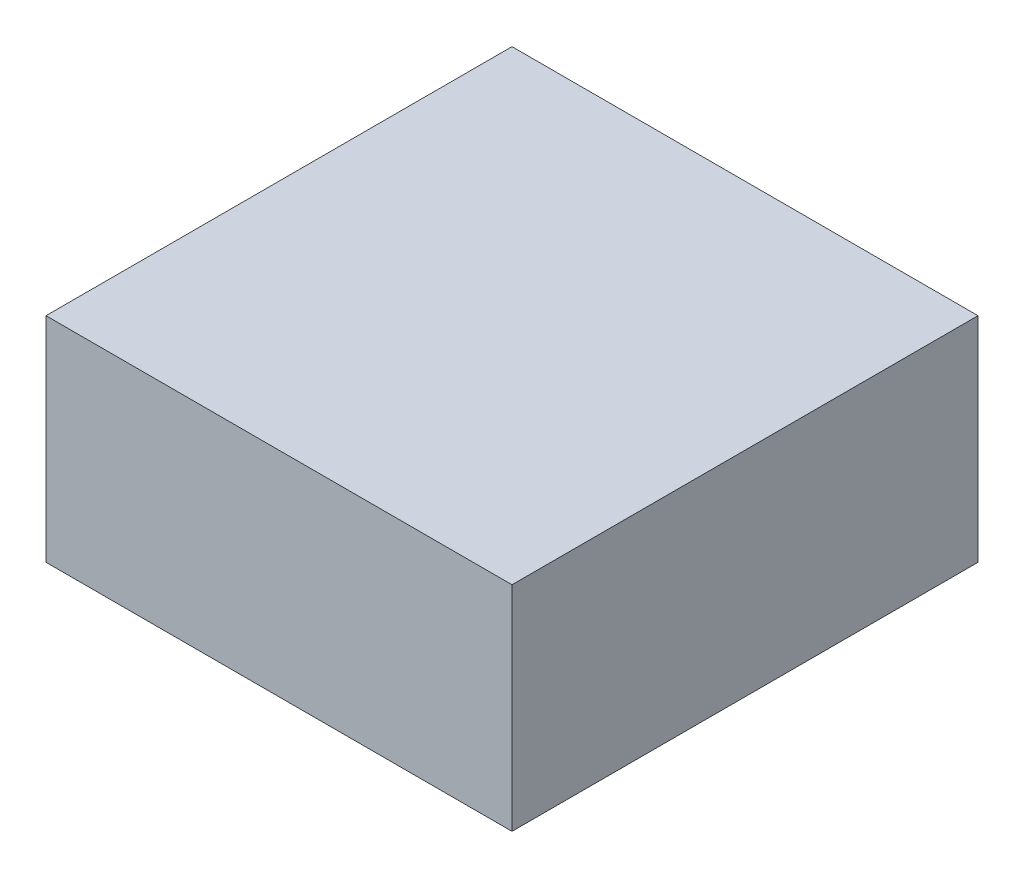
SolidWorks part; units mm, degrees
material "PVC 0.007 Plasticized"
ref_plane "Front Plane" through (0, 0, 0) normal (0, 0, 1) x (1, 0, 0)
ref_plane "Top Plane" through (0, 0, 0) normal (0, 1, 0) x (1, 0, 0)
ref_plane "Right Plane" through (0, 0, 0) normal (1, 0, 0) x (0, 0, -1)
sketch "Sketch1" plane through (0, 0, 0) normal (0, 1, 0) x (1, 0, 0)
  line L0 (-6, 6) -> (-6, -6)
  line L1 (-6, -6) -> (6, -6)
  line L2 (6, -6) -> (6, 6)
  line L3 (6, 6) -> (-6, 6)
  point P4 (0, 6)
  point P6 (6, 0)
  point P7 (6, -5.5327)
  dimension "D1" = 12
extrude "Boss-Extrude1" add sketch "Sketch1" against normal blind 5.5
sketch "Sketch2" plane through (0, -5.5, 0) normal (0, -1, 0) x (1, 0, 0)
  line L0 (5.5, 5.5) -> (-5.5, 5.5)
  line L1 (-5.5, 5.5) -> (-5.5, -5.5)
  line L2 (-5.5, -5.5) -> (5.5, -5.5)
  line L3 (5.5, -5.5) -> (5.5, 5.5)
  line L4 (6, 6) -> (6, -6) construction
  line L5 (-6, -6) -> (-6, 6) construction
  line L6 (-6, 6) -> (6, 6) construction
  line L7 (6, -6) -> (-6, -6) construction
  dimension "D1" = 0.5
  dimension "D2" = 0.5
  dimension "D3" = 0.5
  dimension "D4" = 0.5
extrude "Cut-Extrude1" cut sketch "Sketch2" against normal blind 5
sketch "Sketch3" plane through (0, -0.5, 0) normal (0, -1, 0) x (1, 0, 0)
  line L0 (-2.4, -2.4) -> (-2.4, 2.4)
  line L1 (-2.4, 2.4) -> (2.4, 2.4)
  line L2 (2.4, 2.4) -> (2.4, -2.4)
  line L3 (2.4, -2.4) -> (-2.4, -2.4)
extrude "Boss-Extrude2" add sketch "Sketch3" along normal blind 2.2
sketch "Sketch4" plane through (0, -2.7, 0) normal (0, -1, 0) x (1, 0, 0)
  line L0 (-2.4, -1.9) -> (-2.4, 1.9)
  line L1 (-2.4, 1.9) -> (-1.9, 1.9)
  line L2 (-1.9, 1.9) -> (-1.9, -1.9)
  line L3 (-1.9, -1.9) -> (-2.4, -1.9)
extrude "Boss-Extrude3" add sketch "Sketch4" along normal blind 2.8
sketch "Sketch5" plane through (0, -2.7, 0) normal (0, -1, 0) x (1, 0, 0)
  line L0 (2.4, 1.9) -> (2.4, -1.9)
  line L1 (2.4, -1.9) -> (1.9, -1.9)
  line L2 (1.9, -1.9) -> (1.9, 1.9)
  line L3 (1.9, 1.9) -> (2.4, 1.9)
extrude "Boss-Extrude4" add sketch "Sketch5" along normal blind 2.8
